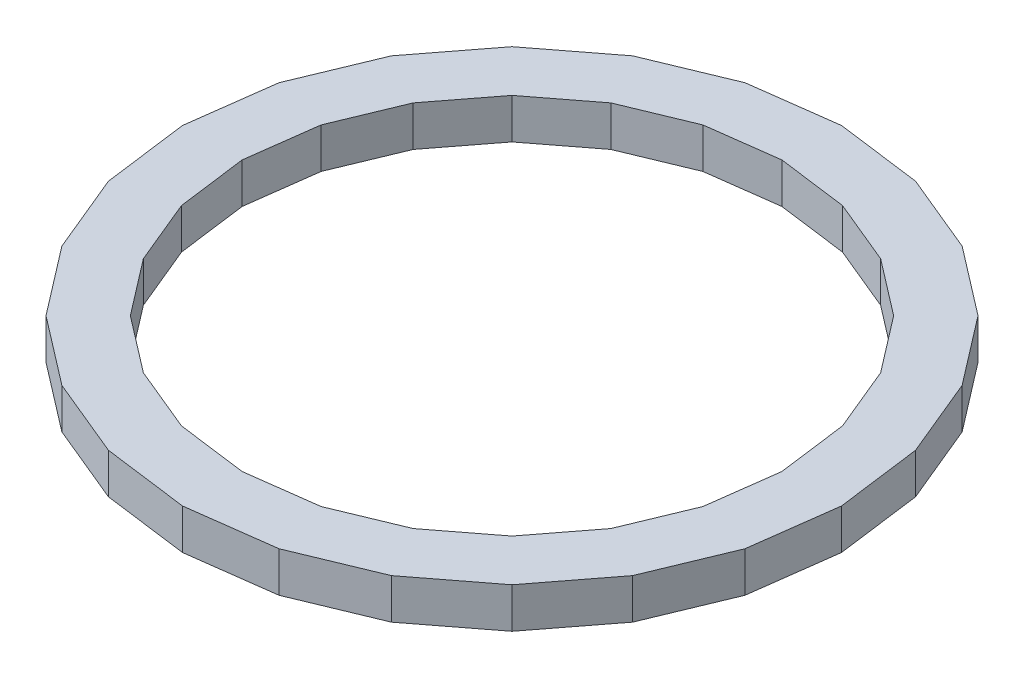
SolidWorks part; units mm, degrees
ref_plane "Front Plane" through (0, 0, 0) normal (0, 0, 1) x (1, 0, 0)
ref_plane "Top Plane" through (0, 0, 0) normal (0, 1, 0) x (1, 0, 0)
ref_plane "Right Plane" through (0, 0, 0) normal (1, 0, 0) x (0, 0, -1)
sketch "Sketch3" plane through (0, 0, 0) normal (0, 1, 0) x (1, 0, 0)
  line L0 (0, 0) -> (-127.4965, 0) construction
  line L1 (-155.6776, 0) -> (-150.373, -40.2923)
  line L2 (-150.373, -40.2923) -> (-134.8207, -77.8388)
  line L3 (-134.8207, -77.8388) -> (-110.0807, -110.0807)
  line L4 (-110.0807, -110.0807) -> (-77.8388, -134.8207)
  line L5 (-77.8388, -134.8207) -> (-40.2923, -150.373)
  line L6 (-40.2923, -150.373) -> (0, -155.6776)
  line L7 (0, -155.6776) -> (40.2923, -150.373)
  line L8 (40.2923, -150.373) -> (77.8388, -134.8207)
  line L9 (77.8388, -134.8207) -> (110.0807, -110.0807)
  line L10 (110.0807, -110.0807) -> (134.8207, -77.8388)
  line L11 (134.8207, -77.8388) -> (150.373, -40.2923)
  line L12 (150.373, -40.2923) -> (155.6776, 0)
  line L13 (155.6776, 0) -> (150.373, 40.2923)
  line L14 (150.373, 40.2923) -> (134.8207, 77.8388)
  line L15 (134.8207, 77.8388) -> (110.0807, 110.0807)
  line L16 (110.0807, 110.0807) -> (77.8388, 134.8207)
  line L17 (77.8388, 134.8207) -> (40.2923, 150.373)
  line L18 (40.2923, 150.373) -> (0, 155.6776)
  line L19 (0, 155.6776) -> (-40.2923, 150.373)
  line L20 (-40.2923, 150.373) -> (-77.8388, 134.8207)
  line L21 (-77.8388, 134.8207) -> (-110.0807, 110.0807)
  line L22 (-110.0807, 110.0807) -> (-134.8207, 77.8388)
  line L23 (-134.8207, 77.8388) -> (-150.373, 40.2923)
  line L24 (-150.373, 40.2923) -> (-155.6776, 0)
  line L25 (-127.4965, 0) -> (-123.1521, -32.9985)
  line L26 (-123.1521, -32.9985) -> (-110.4152, -63.7482)
  line L27 (-110.4152, -63.7482) -> (-90.1536, -90.1536)
  line L28 (-90.1536, -90.1536) -> (-63.7482, -110.4152)
  line L29 (-63.7482, -110.4152) -> (-32.9985, -123.1521)
  line L30 (-32.9985, -123.1521) -> (0, -127.4965)
  line L31 (0, -127.4965) -> (32.9985, -123.1521)
  line L32 (32.9985, -123.1521) -> (63.7482, -110.4152)
  line L33 (63.7482, -110.4152) -> (90.1536, -90.1536)
  line L34 (90.1536, -90.1536) -> (110.4152, -63.7482)
  line L35 (110.4152, -63.7482) -> (123.1521, -32.9985)
  line L36 (123.1521, -32.9985) -> (127.4965, 0)
  line L37 (127.4965, 0) -> (123.1521, 32.9985)
  line L38 (123.1521, 32.9985) -> (110.4152, 63.7482)
  line L39 (110.4152, 63.7482) -> (90.1536, 90.1536)
  line L40 (90.1536, 90.1536) -> (63.7482, 110.4152)
  line L41 (63.7482, 110.4152) -> (32.9985, 123.1521)
  line L42 (32.9985, 123.1521) -> (0, 127.4965)
  line L43 (0, 127.4965) -> (-32.9985, 123.1521)
  line L44 (-32.9985, 123.1521) -> (-63.7482, 110.4152)
  line L45 (-63.7482, 110.4152) -> (-90.1536, 90.1536)
  line L46 (-90.1536, 90.1536) -> (-110.4152, 63.7482)
  line L47 (-110.4152, 63.7482) -> (-123.1521, 32.9985)
  line L48 (-123.1521, 32.9985) -> (-127.4965, 0)
  line L49 (-155.6776, 0) -> (-127.4965, 0) construction
  circle A0 centre (0, 0) radius 154.3457 construction
  circle A1 centre (0, 0) radius 126.4057 construction
  dimension "D1" = 40.64
  dimension "D2" = 27.94
extrude "Boss-Extrude3" add sketch "Sketch3" along normal blind 19.05
